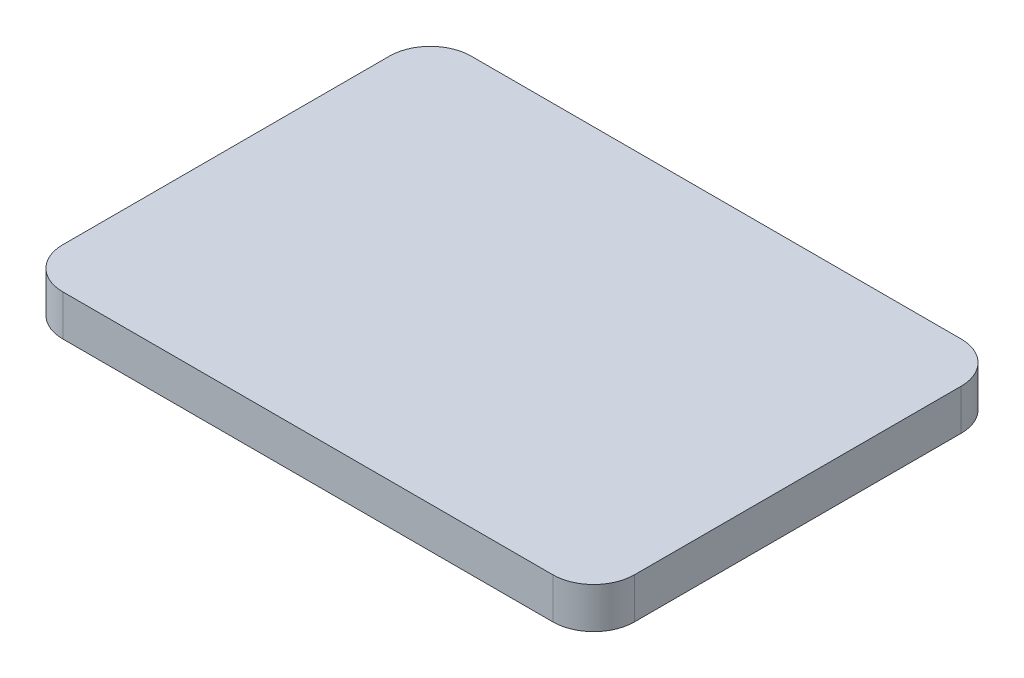
SolidWorks part; units mm, degrees
material "Acrylic (Medium-high impact)"
ref_plane "Front Plane" through (0, 0, 0) normal (0, 0, 1) x (1, 0, 0)
ref_plane "Top Plane" through (0, 0, 0) normal (0, 1, 0) x (1, 0, 0)
ref_plane "Right Plane" through (0, 0, 0) normal (1, 0, 0) x (0, 0, -1)
sketch "Sketch1" plane through (0, 0, 0) normal (0, 1, 0) x (1, 0, 0)
  line L1 (5, 0) -> (65, 0)
  line L2 (0, 5) -> (0, 45)
  line L3 (5, 50) -> (65, 50)
  line L4 (70, 5) -> (70, 45)
  arc A0 (65, 50) -> (70, 45) centre (65, 45) cw
  arc A1 (65, 0) -> (70, 5) centre (65, 5) ccw
  arc A2 (5, 0) -> (0, 5) centre (5, 5) cw
  arc A3 (0, 45) -> (5, 50) centre (5, 45) cw
  point P19 (75, 0)
  point P22 (0, 0)
  point P25 (0, 50)
  dimension "D3" = 5
  dimension "D2" = 70
  dimension "D6" = 50
extrude "Boss-Extrude1" add sketch "Sketch1" along normal blind 5
